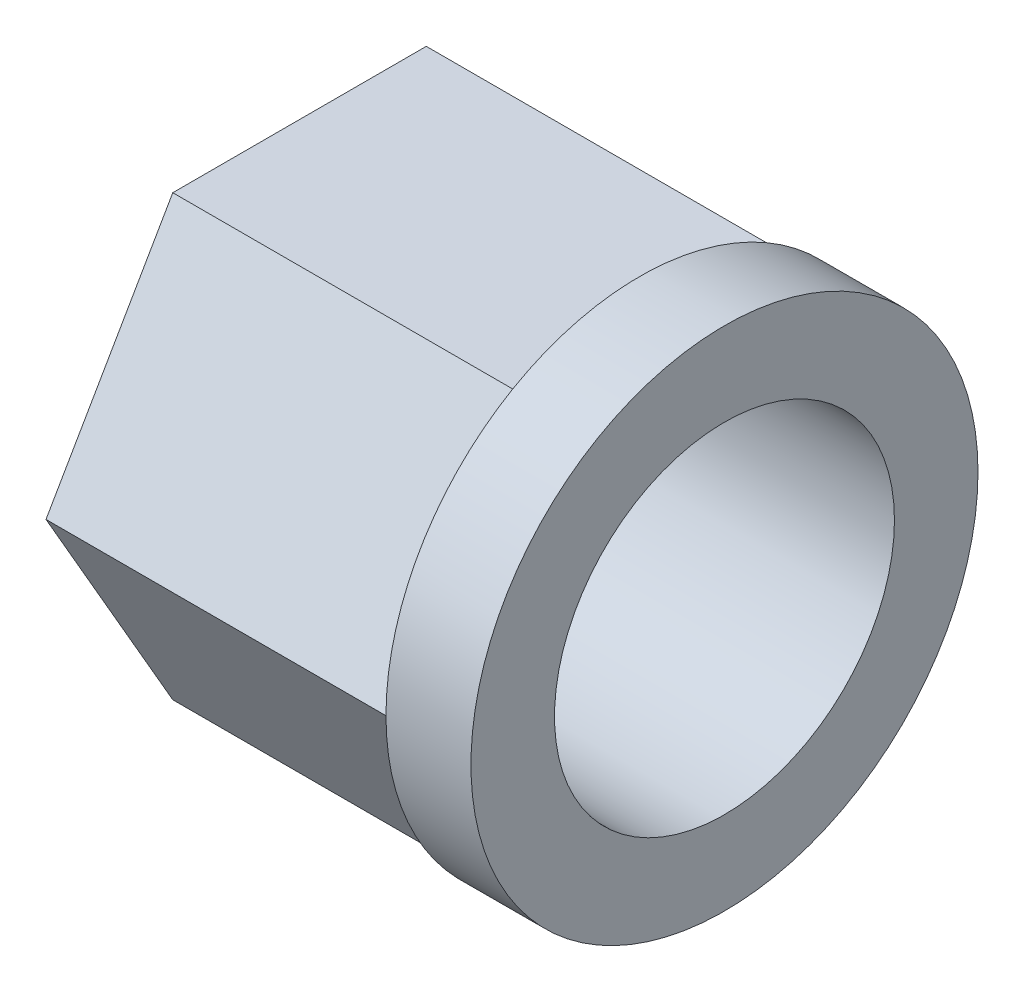
SolidWorks part; units mm, degrees
ref_plane "Front Plane" through (0, 0, 0) normal (0, 0, 1) x (1, 0, 0)
ref_plane "Top Plane" through (0, 0, 0) normal (0, 1, 0) x (1, 0, 0)
ref_plane "Right Plane" through (0, 0, 0) normal (1, 0, 0) x (0, 0, -1)
sketch "Sketch1" plane through (0, 0, 0) normal (1, 0, 0) x (0, 0, -1)
  line L1 (8.9489, 0) -> (4.4745, 7.75)
  line L2 (4.4745, 7.75) -> (-4.4745, 7.75)
  line L3 (-4.4745, 7.75) -> (-8.9489, 0)
  line L4 (-8.9489, 0) -> (-4.4745, -7.75)
  line L5 (-4.4745, -7.75) -> (4.4745, -7.75)
  line L6 (4.4745, -7.75) -> (8.9489, 0)
  circle A0 centre (0, 0) radius 7.75 construction
  dimension "D1" = 7.75
extrude "Boss-Extrude1" add sketch "Sketch1" along normal blind 12
sketch "Sketch2" plane through (12, 0, 0) normal (1, 0, 0) x (0, 0, -1)
  circle A0 centre (0, 0) radius 8.9489
extrude "Boss-Extrude2" add sketch "Sketch2" along normal blind 3
sketch "Sketch3" plane through (15, 0, 0) normal (1, 0, 0) x (0, 0, -1)
  circle A0 centre (0, 0) radius 3.175
  dimension "D1" = 6.35
extrude "Cut-Extrude1" cut sketch "Sketch3" against normal blind 23
sketch "Sketch4" plane through (15, 0, 0) normal (1, 0, 0) x (0, 0, -1)
  circle A0 centre (0, 0) radius 6
  dimension "D1" = 12
extrude "Cut-Extrude2" cut sketch "Sketch4" against normal blind 13
